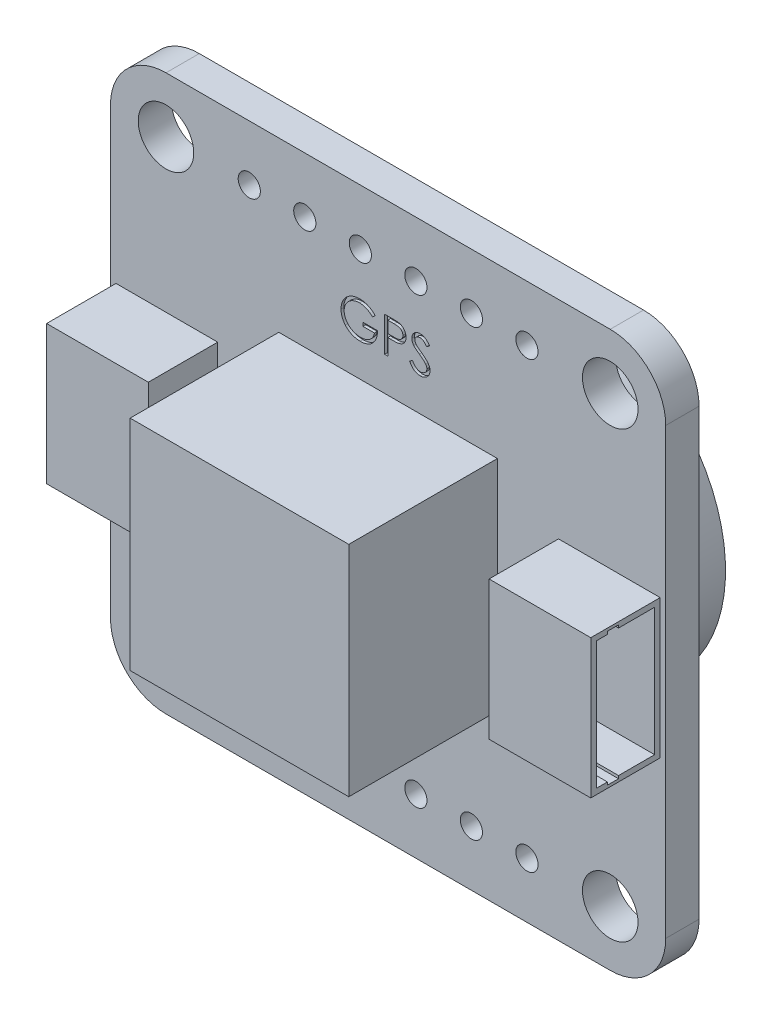
SolidWorks part; units mm, degrees
ref_plane "Front Plane" through (0, 0, 0) normal (0, 0, 1) x (1, 0, 0)
ref_plane "Top Plane" through (0, 0, 0) normal (0, 1, 0) x (1, 0, 0)
ref_plane "Right Plane" through (0, 0, 0) normal (1, 0, 0) x (0, 0, -1)
sketch "Sketch1" plane through (0, 0, 0) normal (0, 0, 1) x (1, 0, 0)
  line L1 (-12.7, -12.7) -> (12.7, -12.7)
  line L2 (-12.7, -12.7) -> (-12.7, 12.7)
  line L3 (-12.7, 12.7) -> (12.7, 12.7)
  line L4 (12.7, -12.7) -> (12.7, 12.7)
  line L5 (-12.7, -12.7) -> (12.7, 12.7) construction
  line L6 (-12.7, 12.7) -> (12.7, -12.7) construction
  point P0 (0, 0)
  dimension "D1" = 25.4
  dimension "D2" = 25.4
extrude "Boss-Extrude1" add sketch "Sketch1" along normal mid plane 1.524
sketch "Sketch2" plane through (0, 0, 0.762) normal (0, 0, 1) x (1, 0, 0)
  line L1 (-12.7, 12.7) -> (-12.7, -12.7) construction
  line L2 (-12.7, -12.7) -> (12.7, -12.7) construction
  line L3 (0.8382, 0) -> (-0.8382, 0) construction
  circle A0 centre (-10.16, 10.16) radius 1.27
  circle A1 centre (10.16, 10.16) radius 1.27
  circle A2 centre (-10.16, -10.16) radius 1.27
  circle A3 centre (10.16, -10.16) radius 1.27
  circle A4 centre (-6.35, 10.16) radius 0.508
  circle A5 centre (-3.81, 10.16) radius 0.508
  circle A6 centre (-1.27, 10.16) radius 0.508
  circle A7 centre (1.27, 10.16) radius 0.508
  circle A8 centre (3.81, 10.16) radius 0.508
  circle A9 centre (6.35, 10.16) radius 0.508
  circle A10 centre (6.35, -10.16) radius 0.508
  circle A11 centre (3.81, -10.16) radius 0.508
  circle A12 centre (1.27, -10.16) radius 0.508
  circle A13 centre (-1.27, -10.16) radius 0.508
  circle A14 centre (-3.81, -10.16) radius 0.508
  circle A15 centre (-6.35, -10.16) radius 0.508
  dimension "D5" = 2.54
  dimension "D6" = 1.016
  dimension "D1" = 20.32
  dimension "D2" = 20.32
  dimension "D3" = 2.54
  dimension "D4" = 2.54
  dimension "D7" = 3.81
  dimension "D8" = 3.81
  dimension "D9" = 2.54
  dimension "D10" = 2.54
  dimension "D11" = 2.54
  dimension "D12" = 2.54
extrude "Cut-Extrude1" cut sketch "Sketch2" against normal through all
sketch "Sketch4" plane through (0, 0, 0.762) normal (0, 0, 1) x (1, 0, 0)
  line L1 (-5, 5) -> (5, 5)
  line L2 (-5, 5) -> (-5, -5)
  line L3 (-5, -5) -> (5, -5)
  line L4 (5, 5) -> (5, -5)
  line L5 (-5, 5) -> (5, -5) construction
  line L6 (-5, -5) -> (5, 5) construction
  point P0 (0, 0)
  dimension "D1" = 10
  dimension "D2" = 10
extrude "Boss-Extrude2" add sketch "Sketch4" along normal blind 6.8
sketch "Sketch5" plane through (0, 0, -0.762) normal (0, 0, -1) x (-1, 0, 0)
  line L0 (2.4426, 5.3639) -> (2.4426, 6.985)
  line L1 (2.4426, -6.985) -> (5.6036, -6.985)
  line L2 (2.4426, -6.985) -> (2.4426, -5.3639)
  line L3 (2.4426, 6.985) -> (5.6036, 6.985)
  line L4 (5.6036, -6.985) -> (5.6036, 6.985)
  line L5 (3.4586, -5.969) -> (3.4586, -2.0455)
  line L6 (3.4586, -5.969) -> (4.5876, -5.969)
  line L7 (4.5876, -5.969) -> (4.5876, 5.969)
  line L8 (3.4586, 5.969) -> (4.5876, 5.969)
  line L9 (3.4586, 2.0455) -> (3.4586, 5.969)
  arc A0 (2.4426, 5.3639) -> (2.4426, -5.3639) centre (-2.4186, 0) ccw
  arc A1 (3.4586, 2.0455) -> (3.4586, -2.0455) centre (-2.4186, 0) ccw
  point P6 (4.0231, 0)
  dimension "D1" = 14.478
  dimension "D2" = 13.97
  dimension "D3" = 1.016
extrude "Boss-Extrude3" add sketch "Sketch5" along normal blind 4.2545
sketch "Sketch6" plane through (0, 0, 0.762) normal (0, 0, 1) x (1, 0, 0)
  line L0 (-5, 5) -> (-5, -5) construction
  line L1 (-12.446, 3.2131) -> (-7.794, 3.2131)
  line L2 (-12.446, 3.2131) -> (-12.446, -3.1369)
  line L3 (-12.446, -3.1369) -> (-7.794, -3.1369)
  line L4 (-7.794, 3.2131) -> (-7.794, -3.1369)
  line L5 (7.794, 3.2131) -> (12.446, 3.2131)
  line L6 (7.794, 3.2131) -> (7.794, -3.1369)
  line L7 (7.794, -3.1369) -> (12.446, -3.1369)
  line L8 (12.446, 3.2131) -> (12.446, -3.1369)
  line L9 (5, -5) -> (5, 5) construction
  line L10 (-12.7, 12.7) -> (-12.7, -12.7) construction
  line L11 (12.7, -12.7) -> (12.7, 12.7) construction
  line L12 (-12.7, -12.7) -> (12.7, -12.7) construction
  dimension "D1" = 6.35
  dimension "D2" = 2.794
  dimension "D3" = 2.794
  dimension "D4" = 0.254
  dimension "D5" = 0.254
  dimension "D6" = 9.5631
extrude "Boss-Extrude4" add sketch "Sketch6" along normal blind 3.175
sketch "Sketch7" plane through (-12.446, 0, 0) normal (-1, 0, 0) x (0, 0, 1)
  line L0 (3.937, 3.2131) -> (0.762, 3.2131) construction
  line L1 (1.016, -2.8829) -> (2.667, -2.8829)
  line L2 (1.016, -2.8829) -> (1.016, 2.9591)
  line L3 (1.016, 2.9591) -> (2.667, 2.9591)
  line L4 (3.683, -2.8829) -> (3.683, 2.9591)
  line L5 (1.016, -2.8829) -> (3.683, 2.9591) construction
  line L6 (1.016, 2.9591) -> (3.683, -2.8829) construction
  line L7 (3.937, -3.1369) -> (0.762, -3.1369) construction
  line L8 (3.937, 3.2131) -> (3.937, -3.1369) construction
  line L9 (0.762, 3.2131) -> (0.762, -3.1369) construction
  line L10 (3.175, 2.9591) -> (3.683, 2.9591)
  line L12 (3.175, 2.9591) -> (3.175, 3.0861)
  line L13 (3.175, 3.0861) -> (2.667, 3.0861)
  line L14 (2.667, 2.9591) -> (2.667, 3.0861)
  line L16 (3.175, -2.8829) -> (3.175, -3.0099)
  line L17 (3.175, -3.0099) -> (2.667, -3.0099)
  line L18 (2.667, -2.8829) -> (2.667, -3.0099)
  line L19 (3.175, -2.8829) -> (3.683, -2.8829)
  point P0 (2.3495, 0.0381)
  dimension "D1" = 0.254
  dimension "D2" = 0.254
  dimension "D3" = 0.254
  dimension "D4" = 0.254
  dimension "D5" = 0.508
  dimension "D6" = 0.508
  dimension "D7" = 0.127
extrude "Cut-Extrude2" cut sketch "Sketch7" against normal blind 3.175
mirror "Mirror1" about plane through (0, 0, 0) normal (1, 0, 0) of "Cut-Extrude2"
fillet "Fillet1" radius 2.54 4 edges at (12.7, -12.7, 0) (-12.7, -12.7, 0) (-12.7, 12.7, 0) (12.7, 12.7, 0)
sketch "Sketch8" plane through (0, 0, 0.762) normal (0, 0, 1) x (1, 0, 0)
  line L0 (-2.275, 6.5495) -> (2.805, 6.5495) construction
  text T0 "GPS" font "Century Gothic" height in points 6
  point P8 (0.265, 6.5495)
  dimension "D1" = 5.08
extrude "Cut-Extrude3" cut sketch "Sketch8" against normal blind 0.127
